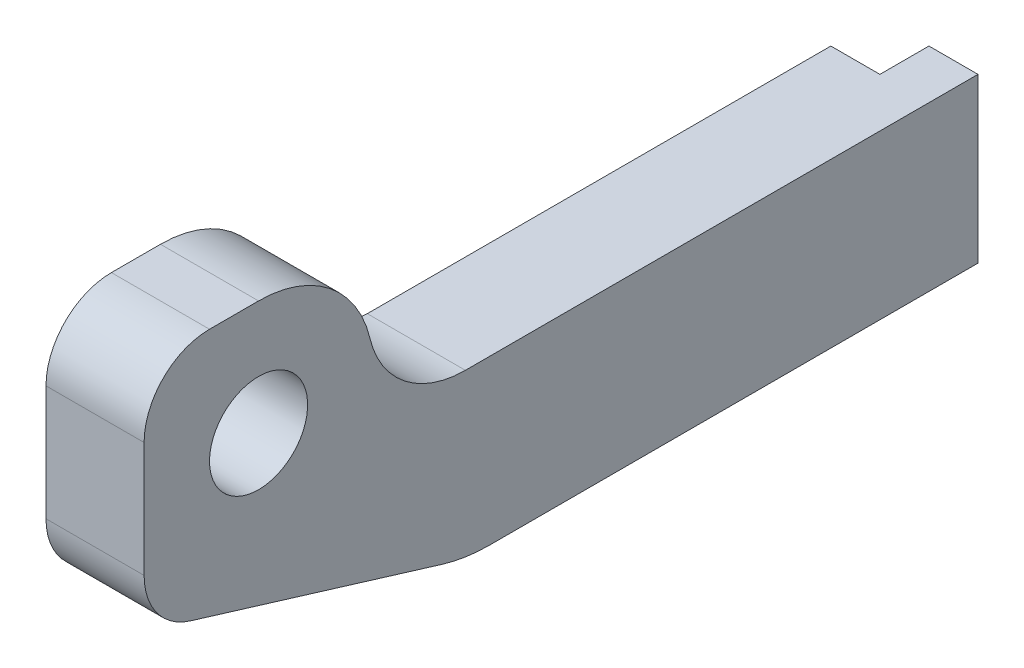
SolidWorks part; units mm, degrees
ref_plane "Front Plane" through (0, 0, 0) normal (0, 0, 1) x (1, 0, 0)
ref_plane "Top Plane" through (0, 0, 0) normal (0, 1, 0) x (1, 0, 0)
ref_plane "Right Plane" through (0, 0, 0) normal (1, 0, 0) x (0, 0, -1)
sketch "Sketch1" plane through (0, 116.5, 0) normal (0, 1, 0) x (1, 0, 0)
  line L0 (-4, 23.815) -> (-2.5, 23.815) construction
  line L1 (-2.5, 23.815) -> (-2.5, 25.315) construction
  line L2 (-2.5, 25.315) -> (-1, 25.315) construction
  line L3 (-1, 25.315) -> (-1, 9.6396) construction
  line L4 (-4, 23.815) -> (-2.5, 23.815)
  line L5 (-2.5, 23.815) -> (-2.5, 25.315)
  line L6 (-2.5, 25.315) -> (-1, 25.315)
  line L7 (-1, 25.315) -> (-1, 9.6396)
  line L8 (-4, 23.815) -> (-4, 9.6396)
  line L9 (-4, 0.815) -> (-4, 22.815) construction
  line L10 (-4, 9.6396) -> (-1, 9.6396)
extrude "Tab extrude" add sketch "Sketch1" against normal up to vertex (5 mm away)
sketch "Sketch2" plane through (-1, 0, 0) normal (-1, 0, 0) x (0, 0, 1)
  line L0 (-9.6396, 111.5) -> (-1.2309, 114.0676)
  line L1 (0.185, 115.9805) -> (0.185, 119.5)
  line L2 (27.522, 121.5) -> (-3.315, 121.5) construction
  line L3 (-1.815, 121.5) -> (-3.315, 121.5)
  line L5 (-9.6396, 111.5) -> (-9.6396, 116.5) construction
  line L6 (-9.6396, 111.5) -> (-9.6396, 116.5)
  arc A0 (-3.315, 121.5) -> (-6.7205, 118.8077) centre (-3.315, 118) ccw construction
  arc A1 (-3.315, 121.5) -> (-6.7205, 118.8077) centre (-3.315, 118) ccw
  circle A2 centre (-3.315, 118) radius 1.5 construction
  circle A3 centre (-3.315, 118) radius 1.5
  arc A4 (-1.2309, 114.0676) -> (0.185, 115.9805) centre (-1.815, 115.9805) ccw
  arc A5 (0.185, 119.5) -> (-1.815, 121.5) centre (-1.815, 119.5) ccw
  arc A6 (-9.6396, 116.5) -> (-6.7205, 118.8077) centre (-9.6396, 119.5) ccw construction
  arc A7 (-9.6396, 116.5) -> (-6.7205, 118.8077) centre (-9.6396, 119.5) ccw
  point P16 (0.185, 114.5)
  point P19 (0.185, 121.5)
  dimension "D1" = 2
extrude "Screwhole extrude" add sketch "Sketch2" along normal up to surface (3 mm away) up to face at (-4, 114, -16.7273)
fillet "Structural fillets" radius 5 1 edges at (-2.5, 111.5, -9.6396)
